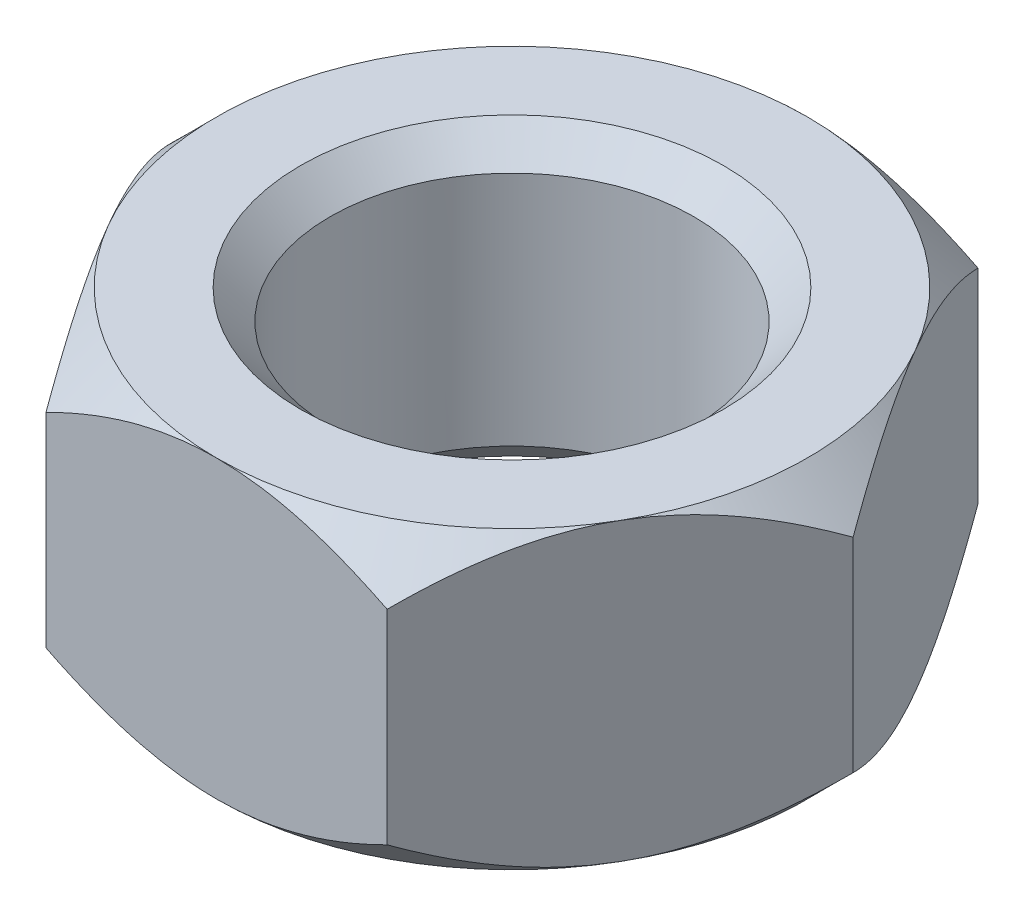
SolidWorks part; units mm, degrees
material "Cast Stainless Steel"
ref_plane "Front Plane" through (0, 0, 0) normal (0, 0, 1) x (1, 0, 0)
ref_plane "Top Plane" through (0, 0, 0) normal (0, 1, 0) x (1, 0, 0)
ref_plane "Right Plane" through (0, 0, 0) normal (1, 0, 0) x (0, 0, -1)
sketch "Sketch1" plane through (0, 0, 0) normal (0, 1, 0) x (1, 0, 0)
  line L0 (-7.5056, 0) -> (7.5056, 0) construction
  line L1 (7.5056, 0) -> (3.7528, 6.5)
  line L2 (3.7528, 6.5) -> (-3.7528, 6.5)
  line L3 (-3.7528, 6.5) -> (-7.5056, 0)
  line L4 (-7.5056, 0) -> (-3.7528, -6.5)
  line L5 (-3.7528, -6.5) -> (3.7528, -6.5)
  line L6 (3.7528, -6.5) -> (7.5056, 0)
  circle A0 centre (0, 0) radius 6.5 construction
  circle A1 centre (0, 0) radius 4
  point P12 (0, 0)
  dimension "D1" = 8
  dimension "D2" = 13
extrude "Boss-Extrude1" add sketch "Sketch1" along normal blind 6.5
sketch "Sketch3" plane through (0, 0, 0) normal (1, 0, 0) x (0, 0, -1)
  line L0 (-6.5, 0) -> (-8.75, 2.25)
  line L1 (-8.75, 2.25) -> (-8.75, 0)
  line L2 (-8.75, 0) -> (-6.5, 0)
  line L4 (-6.5, 3.25) -> (6.5, 3.25) construction
  line L6 (6.5, 6.5) -> (6.5, 0) construction
  line L7 (-8.75, 6.5) -> (-6.5, 6.5)
  line L8 (-8.75, 4.25) -> (-8.75, 6.5)
  line L9 (-6.5, 6.5) -> (-8.75, 4.25)
  line L10 (0, 0) -> (0, 6.5) construction
  line L12 (-6.5, 6.5) -> (-6.5, 0) construction
  point P7 (0, 3.25)
  dimension "D1" = 3.25
  dimension "D2" = 45
  dimension "D3" = 2.25
revolve "Cut-Revolve1" cut sketch "Sketch3" angle 360 about L10
chamfer "Chamfer1" distance 0.65 angle 45 2 edges at (0, 0, 4) (0, 6.5, 4)
equation "\"d\"= 8"
equation "\"m\"= 6.5"
equation "\"s\"= 13"
equation "\"e\"= 14.38"
equation "\"D1@Sketch1\"=\"d\""
equation "\"D2@Sketch1\"=\"s\""
equation "\"D1@Boss-Extrude1\"=\"m\""
equation "\"D1@Sketch3\"=\"m\"/2"
equation "\"D3@Sketch3\"=\"D1@Sketch3\"-1"
equation "\"D1@Chamfer1\"=\"s\"/20"
